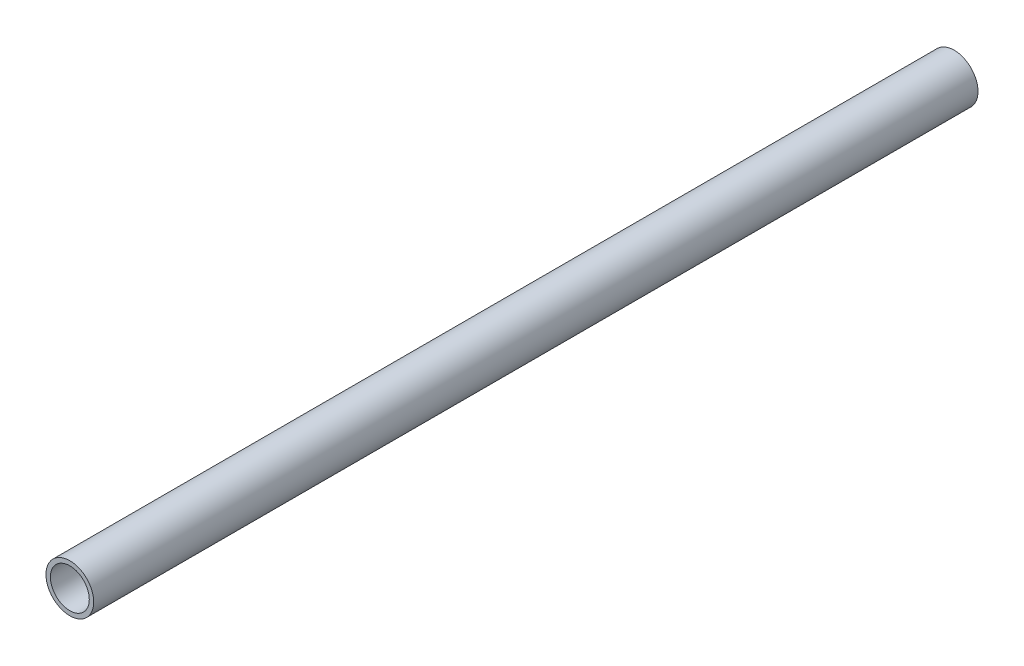
SolidWorks part; units mm, degrees
ref_plane "Alzado" through (0, 0, 0) normal (0, 0, 1) x (1, 0, 0)
ref_plane "Planta" through (0, 0, 0) normal (0, 1, 0) x (1, 0, 0)
ref_plane "Vista lateral" through (0, 0, 0) normal (1, 0, 0) x (0, 0, -1)
sketch "Croquis1" plane through (0, 0, 0) normal (0, 0, 1) x (1, 0, 0)
  circle A0 centre (0, 0) radius 6.6
  circle A1 centre (0, 0) radius 8.1
  dimension "D1" = 16.2
  dimension "D2" = 1.5
extrude "Saliente-Extruir1" add sketch "Croquis1" along normal mid plane 300
